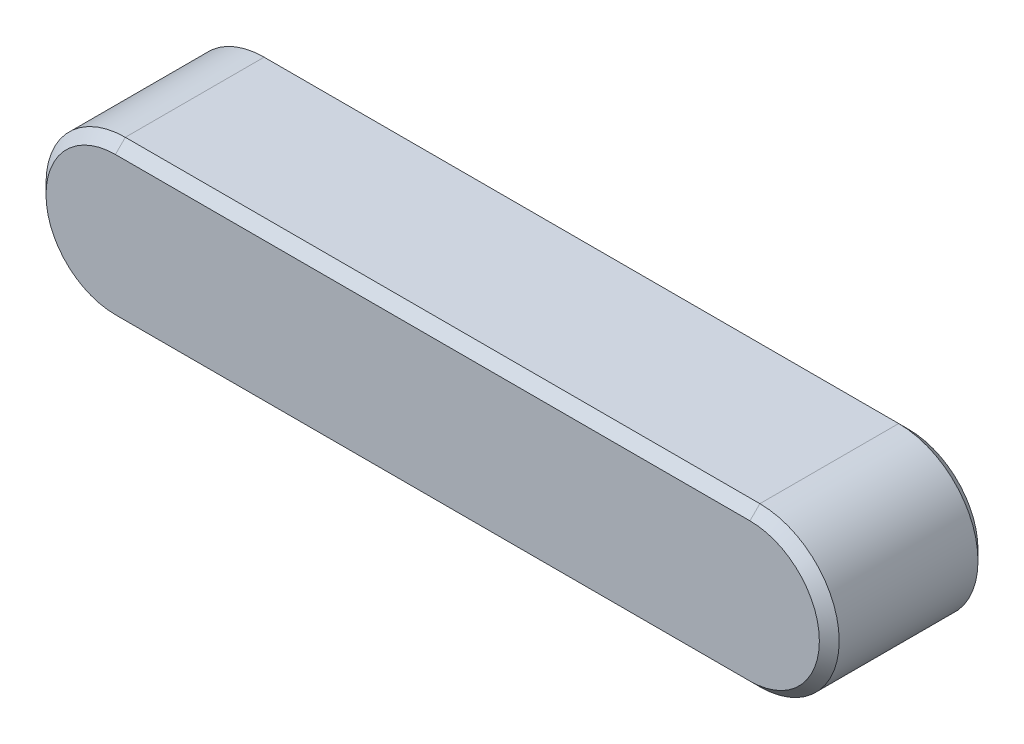
SolidWorks part; units mm, degrees
ref_plane "Front" through (0, 0, 0) normal (0, 0, 1) x (1, 0, 0)
ref_plane "Top" through (0, 0, 0) normal (0, 1, 0) x (1, 0, 0)
ref_plane "Right" through (0, 0, 0) normal (1, 0, 0) x (0, 0, -1)
sketch "Sketch1" plane through (0, 0, 0) normal (0, 0, 1) x (1, 0, 0)
  line L0 (-16, 2) -> (0, 2)
  line L1 (0, -2) -> (-16, -2)
  arc A0 (0, 2) -> (0, -2) centre (0, 0) cw
  arc A1 (-16, -2) -> (-16, 2) centre (-16, 0) cw
  dimension "L" = 20
  dimension "b" = 4
extrude "BaseKey" add sketch "Sketch1" along normal mid plane 4
sketch "Sketch2" plane through (0, 0, 0) normal (0, 0, 1) x (1, 0, 0)
  line L1 (-18, 2) -> (2, 2)
  line L2 (-18, 2) -> (-18, -2)
  line L3 (-18, -2) -> (2, -2)
  line L4 (2, 2) -> (2, -2)
  line L6 (0, -2) -> (-16, -2) construction
  line L7 (-16, 2) -> (0, 2) construction
  arc A2 (0, -2) -> (0, 2) centre (0, 0) ccw construction
  arc A3 (-16, 2) -> (-16, -2) centre (-16, 0) ccw construction
extrude "Extrude1" [suppressed] add sketch "Sketch2" along normal mid plane 4
sketch "Sketch3" plane through (0, 0, 0) normal (0, 0, 1) x (1, 0, 0)
  line L0 (2, 2) -> (-16, 2)
  line L1 (-16, -2) -> (2, -2)
  line L2 (2, -2) -> (2, 2)
  line L5 (-16, 2) -> (0, 2) construction
  arc A0 (-16, 2) -> (-16, -2) centre (-16, 0) ccw
  arc A1 (0, -2) -> (0, 2) centre (0, 0) ccw construction
  arc A4 (-16, 2) -> (-16, -2) centre (-16, 0) ccw construction
extrude "Extrude2" [suppressed] add sketch "Sketch3" along normal mid plane 4
chamfer "Chamfer1" distance 0.25 angle 45 8 edges at (2, 0, -2) (-8, -2, -2) (-18, 0, -2) (-8, 2, -2) (-18, 0, 2) (-8, -2, 2) (2, 0, 2) (-8, 2, 2)
equation "\"D1@Extrude1\"=\"h@BaseKey\""
equation "\"D1@Extrude2\"=\"h@BaseKey\""
